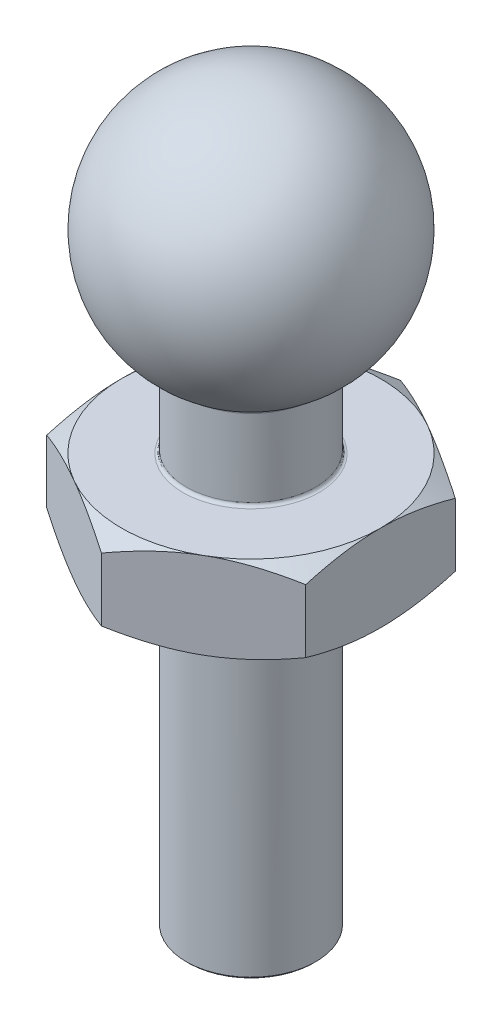
SolidWorks part; units mm, degrees
ref_plane "Front Plane" through (0, 0, 0) normal (0, 0, 1) x (1, 0, 0)
ref_plane "Top Plane" through (0, 0, 0) normal (0, 1, 0) x (1, 0, 0)
ref_plane "Right Plane" through (0, 0, 0) normal (1, 0, 0) x (0, 0, -1)
sketch "Sketch1" plane through (0, 0, 0) normal (0, 0, 1) x (1, 0, 0)
  line L0 (0, 11) -> (0, 17)
  line L1 (0, 0) -> (1.5, 0)
  line L2 (1.5, 0) -> (1.5, 11.4019) construction
  line L3 (0, 11) -> (0, 0)
  line L4 (1.5, 0) -> (1.5, 11.4019)
  circle A0 centre (0, 14) radius 3 construction
  arc A1 (0, 17) -> (1.5, 11.4019) centre (0, 14) cw
  dimension "D1" = 6
  dimension "D2" = 1.5
  dimension "D3" = 11
revolve "Revolve1" add sketch "Sketch1" angle 360 about L3
sketch "Sketch2" plane through (0, 0, 0) normal (0, 0, 1) x (1, 0, 0)
  line L0 (-6.593, 7.5) -> (6.593, 7.5)
  line L1 (-1.5, 0) -> (1.5, 0) construction
  point P5 (0, 7.5)
  dimension "D1" = 7.5
split line "Split Line1"
chamfer "Chamfer17" distance 0.05 angle 45 1 edges at (-1.5, 0, 0)
ref_plane "Plane1" through (0, 7.5, 0) normal (0, 1, 0) x (1, 0, 0)
sketch "Sketch4" plane through (0, 7.5, 0) normal (0, 1, 0) x (1, 0, 0)
  line L1 (0, 3.4641) -> (-3, 1.7321)
  line L2 (-3, 1.7321) -> (-3, -1.7321)
  line L3 (-3, -1.7321) -> (0, -3.4641)
  line L4 (0, -3.4641) -> (3, -1.7321)
  line L5 (3, -1.7321) -> (3, 1.7321)
  line L6 (3, 1.7321) -> (0, 3.4641)
  circle A1 centre (0, 0) radius 3 construction
  dimension "D2" = 6
extrude "Boss-Extrude2" add sketch "Sketch4" along normal blind 2
sketch "Sketch5" plane through (0, 7.5, 0) normal (0, -1, 0) x (1, 0, 0)
  circle A0 centre (0, 0) radius 3 construction
  circle A1 centre (0, 0) radius 3
extrude "Cut-Extrude1" cut sketch "Sketch5" against normal blind 2 draft 60 flip side to cut
sketch "Sketch6" plane through (0, 9.5, 0) normal (0, 1, 0) x (1, 0, 0)
  circle A1 centre (0, 0) radius 3
  circle A2 centre (0, 0) radius 3
  dimension "D1" = 0
extrude "Cut-Extrude2" cut sketch "Sketch6" against normal blind 2 draft 60 flip side to cut contours A2
fillet "Fillet2" radius 0.075 2 edges at (-1.5, 11.4019, 0) (0, 9.5, 1.5)
